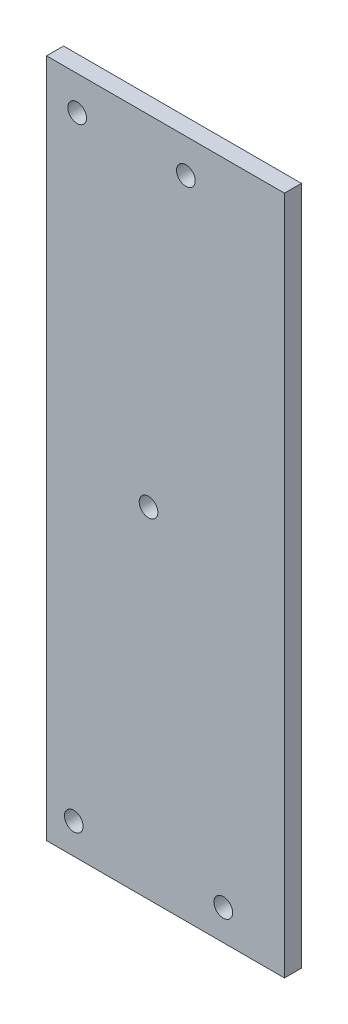
SolidWorks part; units mm, degrees
ref_plane "정면" through (0, 0, 0) normal (0, 0, 1) x (1, 0, 0)
ref_plane "윗면" through (0, 0, 0) normal (0, 1, 0) x (1, 0, 0)
ref_plane "우측면" through (0, 0, 0) normal (1, 0, 0) x (0, 0, -1)
sketch "스케치1" plane through (0, 0, 0) normal (0, 0, 1) x (1, 0, 0)
  line L1 (-50, 100) -> (50, 100)
  line L2 (-50, 100) -> (-50, -100)
  line L3 (-50, -100) -> (50, -100)
  line L4 (50, 100) -> (50, -100)
  line L5 (-50, 100) -> (50, -100) construction
  line L6 (-50, -100) -> (50, 100) construction
  point P0 (0, 0)
  dimension "D1" = 100
  dimension "D2" = 200
extrude "보스-돌출1" add sketch "스케치1" along normal blind 5
sketch "스케치3" plane through (0, 0, 0) normal (0, 0, -1) x (-1, 0, 0)
  text T0 "front"
extrude "컷-돌출2" cut sketch "스케치3" against normal blind 0.001
ref_plane "평면1" through (0, 0, -5) normal (0, 0, -1) x (-1, 0, 0)
sketch "스케치13" plane through (0, 0, 5) normal (0, 0, 1) x (1, 0, 0)
  line L0 (-50, -100) -> (50, -100) construction
  line L1 (50, 100) -> (40, 100)
  line L2 (50, 100) -> (50, -100)
  line L3 (50, -100) -> (40, -100)
  line L4 (40, 100) -> (40, -100)
  line L5 (0, -2.75) -> (0, 2.75) construction
  line L6 (-40, 100) -> (-40, -100)
  line L7 (-50, -100) -> (-40, -100)
  line L8 (-50, 100) -> (-50, -100)
  line L9 (-50, 100) -> (-40, 100)
  dimension "D1" = 10
extrude "컷-돌출4" cut sketch "스케치13" against normal blind 10
sketch "스케치14" plane through (0, 0, 5) normal (0, 0, 1) x (1, 0, 0)
  line L0 (-40, -100) -> (40, -100) construction
  line L1 (40, 100) -> (30, 100)
  line L2 (40, 100) -> (40, -100)
  line L3 (40, -100) -> (30, -100)
  line L4 (30, 100) -> (30, -100)
  dimension "D1" = 10
extrude "컷-돌출5" cut sketch "스케치14" against normal blind 10
sketch "스케치15" plane through (0, 0, 0) normal (0, 0, -1) x (-1, 0, 0)
  line L1 (-30, 100) -> (40, 100) construction
  line L2 (40, -100) -> (40, 100) construction
  circle A0 centre (-1, 90) radius 2.75
  circle A1 centre (31, 90) radius 2.75
  dimension "D2" = 5.5
  dimension "D3" = 5.5
  dimension "D1" = 9
  dimension "D4" = 41
  dimension "D5" = 10
  dimension "D6" = 10
extrude "컷-돌출6" cut sketch "스케치15" against normal through all
sketch "스케치17" plane through (0, 0, 0) normal (0, 0, -1) x (-1, 0, 0)
  line L0 (40, -100) -> (-30, -100) construction
  line L2 (-30, 100) -> (-30, -100) construction
  circle A1 centre (10, 0) radius 2.75
  point P10 (0, 0)
  dimension "D4" = 5.5
  dimension "D5" = 40
  dimension "D6" = 100
extrude "컷-돌출8" cut sketch "스케치17" against normal blind 10
sketch "스케치18" plane through (0, 0, 0) normal (0, 0, -1) x (-1, 0, 0)
  line L0 (-30, 100) -> (-30, -100) construction
  line L1 (40, -100) -> (40, 100) construction
  line L3 (40, -100) -> (-30, -100) construction
  circle A0 centre (32, -91) radius 2.75
  circle A1 centre (-12, -91) radius 2.75
  point P10 (34.1473, -100)
  dimension "D1" = 5.5
  dimension "D2" = 5.5
  dimension "D3" = 18
  dimension "D4" = 8
  dimension "D5" = 9
  dimension "D6" = 9
extrude "컷-돌출9" cut sketch "스케치18" against normal blind 10
